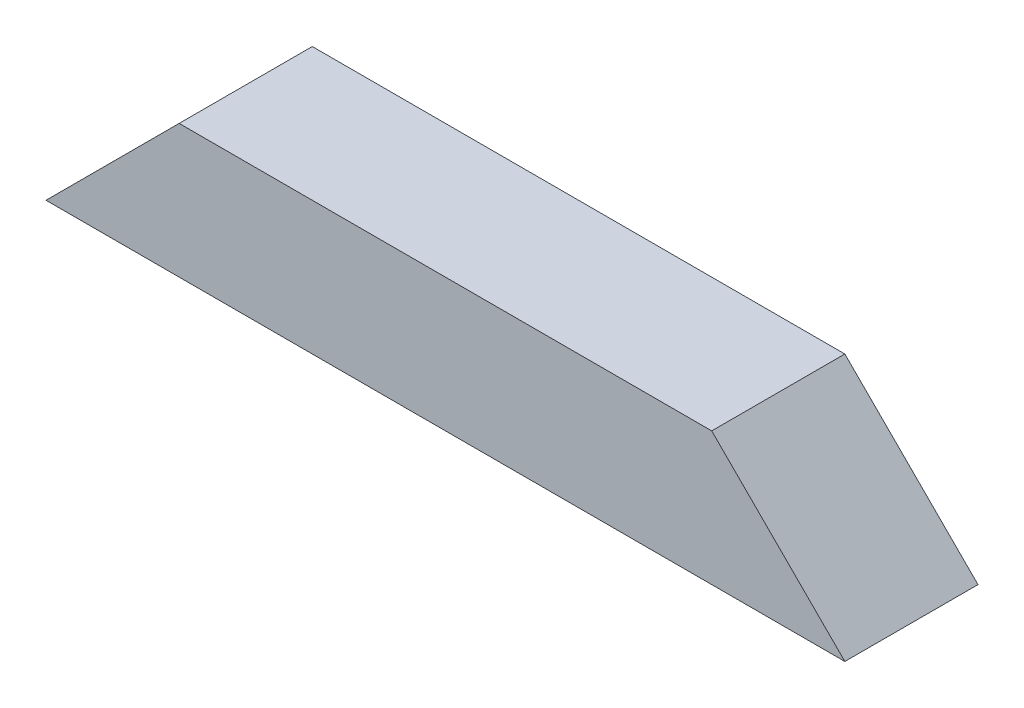
SolidWorks part; units mm, degrees
ref_plane "Alzado" through (0, 0, 0) normal (0, 0, 1) x (1, 0, 0)
ref_plane "Planta" through (0, 0, 0) normal (0, 1, 0) x (1, 0, 0)
ref_plane "Vista lateral" through (0, 0, 0) normal (1, 0, 0) x (0, 0, -1)
sketch "Croquis1" plane through (0, 0, 0) normal (0, 0, 1) x (1, 0, 0)
  line L1 (152.4, -25.4) -> (-152.4, -25.4)
  line L2 (152.4, -25.4) -> (152.4, 25.4)
  line L3 (152.4, 25.4) -> (-152.4, 25.4)
  line L4 (-152.4, -25.4) -> (-152.4, 25.4)
  line L5 (152.4, -25.4) -> (-152.4, 25.4) construction
  line L6 (152.4, 25.4) -> (-152.4, -25.4) construction
  point P0 (0, 0)
  dimension "D1" = 304.8
  dimension "D2" = 50.8
extrude "Saliente-Extruir1" add sketch "Croquis1" along normal blind 50.8
sketch "Croquis2" plane through (0, 0, 50.8) normal (0, 0, 1) x (1, 0, 0)
  line L0 (-152.4, -25.4) -> (152.4, -25.4) construction
  line L1 (-152.4, 25.4) -> (-132.4, 25.4)
  line L2 (-152.4, 25.4) -> (-152.4, -25.4)
  line L3 (-152.4, -25.4) -> (-132.4, -25.4)
  line L4 (-132.4, 25.4) -> (-132.4, -25.4)
  line L5 (-152.4, -25.4) -> (-132.4, 25.4)
  line L6 (0, 0) -> (0, 43.7093) construction
  line L7 (152.4, 25.4) -> (152.4, -25.4)
  line L8 (152.4, -25.4) -> (132.4, 25.4)
  line L9 (152.4, 25.4) -> (132.4, 25.4)
  line M5 (-152.4, 25.4) -> (-152.4, -25.4)
  line M7 (152.4, -25.4) -> (152.4, 25.4)
  line M8 (152.4, 25.4) -> (-152.4, 25.4)
  dimension "D1" = 20
extrude "Cortar-Extruir1" cut sketch "Croquis2" against normal through all contours L5 M5 M8 | L8 M7 M8
sketch "Croquis3" plane through (0, 0, 50.8) normal (0, 0, 1) x (1, 0, 0)
  line L0 (132.4, 25.4) -> (-132.4, 25.4) construction
  line L1 (-152.4, -25.4) -> (-101.6, -25.4)
  line L2 (-152.4, -25.4) -> (-152.4, 25.4)
  line L3 (-152.4, 25.4) -> (-101.6, 25.4)
  line L4 (-101.6, -25.4) -> (-101.6, 25.4)
  line L5 (-152.4, -25.4) -> (-101.6, 25.4)
  line L6 (0, 0) -> (0, 136.2627) construction
  line L7 (152.4, -25.4) -> (101.6, 25.4)
  line L8 (152.4, -25.4) -> (152.4, 25.4)
  line L9 (152.4, 25.4) -> (101.6, 25.4)
  line M6 (152.4, -25.4) -> (132.4, 25.4)
  line M7 (132.4, 25.4) -> (-132.4, 25.4)
  line M8 (-132.4, 25.4) -> (-152.4, -25.4)
  dimension "D1" = 50.8
extrude "Cortar-Extruir2" cut sketch "Croquis3" against normal through all contours L5 M8 M7 | L7 M6 M7
